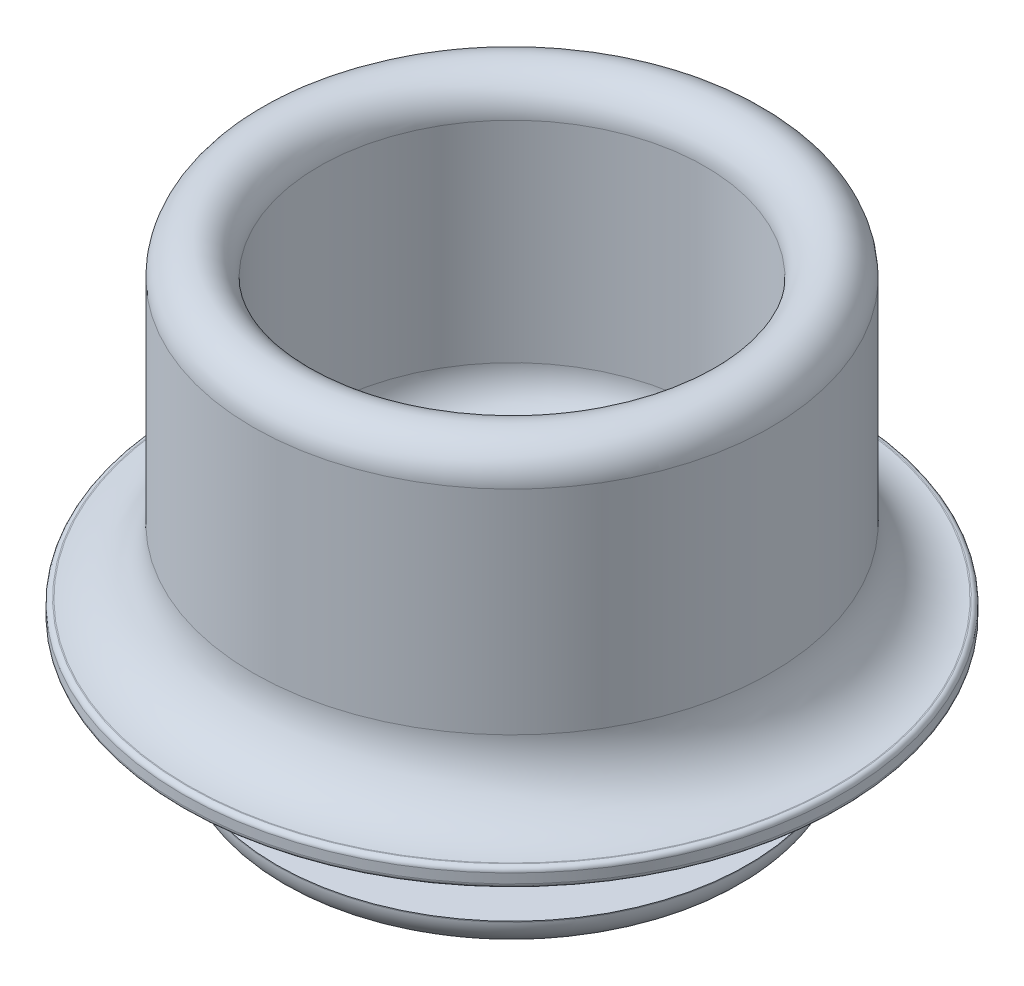
SolidWorks part; units mm, degrees
material "AISI 1020"
ref_plane "Plan de face" through (0, 0, 0) normal (0, 0, 1) x (1, 0, 0)
ref_plane "Plan de dessus" through (0, 0, 0) normal (0, 1, 0) x (1, 0, 0)
ref_plane "Plan de droite" through (0, 0, 0) normal (1, 0, 0) x (0, 0, -1)
sketch "Esquisse1" plane through (0, 0, 0) normal (0, 0, 1) x (1, 0, 0)
  line L0 (0, 1.5132) -> (0, -2.069) construction
  line L1 (0, 0) -> (0, 0.3)
  line L2 (0, 0.3) -> (-0.0089, 0.3)
  line L3 (-0.1589, 0.45) -> (-0.1589, 0.46)
  line L4 (-0.4089, 0.71) -> (-1, 0.71)
  line L5 (-1.25, 0.46) -> (-1.25, 0.47)
  line L6 (-1.25, 0.47) -> (-1.6, 0.47)
  line L7 (-2.05, 0.92) -> (-2.05, 3.15)
  line L8 (-2.4, 3.717) -> (-2.4, -0.1924) construction
  line L9 (-2.3413, 3.15) -> (-1.1479, 3.15) construction
  line L10 (-2.75, 3.15) -> (-2.75, 0.89)
  line L11 (-1.5, 0) -> (-3.45, 0)
  line L12 (-3.5, 0.05) -> (-3.5, 0.15)
  line L13 (-3.45, 0.2) -> (-3.44, 0.2)
  line L14 (-1.5, 0) -> (-1.5, -1)
  line L15 (0, 0) -> (0, -1.16)
  line L16 (-1.5, -1) -> (-2.5011, -1)
  line L17 (-2.5011, -1) -> (-2.5011, -1.01)
  line L18 (-2.2011, -1.31) -> (-0.15, -1.31)
  arc A0 (-0.0089, 0.3) -> (-0.1589, 0.45) centre (-0.0089, 0.45) cw
  arc A1 (-2.05, 3.15) -> (-2.75, 3.15) centre (-2.4, 3.15) ccw
  arc A2 (-3.5, 0.15) -> (-3.45, 0.2) centre (-3.45, 0.15) cw
  arc A3 (-3.45, 0) -> (-3.5, 0.05) centre (-3.45, 0.05) cw
  arc A4 (-1.6, 0.47) -> (-2.05, 0.92) centre (-1.6, 0.92) cw
  arc A5 (-0.1589, 0.46) -> (-0.4089, 0.71) centre (-0.4089, 0.46) ccw
  arc A6 (-1, 0.71) -> (-1.25, 0.46) centre (-1, 0.46) ccw
  arc A7 (-3.44, 0.2) -> (-2.75, 0.89) centre (-3.44, 0.89) ccw
  arc A8 (0, -1.16) -> (-0.15, -1.31) centre (0, -1.31) ccw
  arc A9 (-2.5011, -1.01) -> (-2.2011, -1.31) centre (-2.2011, -1.01) ccw
  dimension "D2" = 0.15
  dimension "D7" = 0.05
  dimension "D8" = 0.45
  dimension "D9" = 0.25
  dimension "D14" = 0.69
  dimension "D17" = 0.3
  dimension "D20" = 0.3
  dimension "D1" = 0.3
  dimension "D3" = 0.35
  dimension "D4" = 3.15
  dimension "D5" = 2.4
  dimension "D6" = 0.2
  dimension "D10" = 0.71
  dimension "D11" = 0.47
  dimension "D12" = 1.25
  dimension "D13" = 3.5
  dimension "D15" = 0.4089
  dimension "D16" = 1.5
  dimension "D18" = 1
  dimension "D19" = 0.31
  dimension "D21" = 2.5011
revolve "Révolution1" add sketch "Esquisse1" angle 360 about L0
